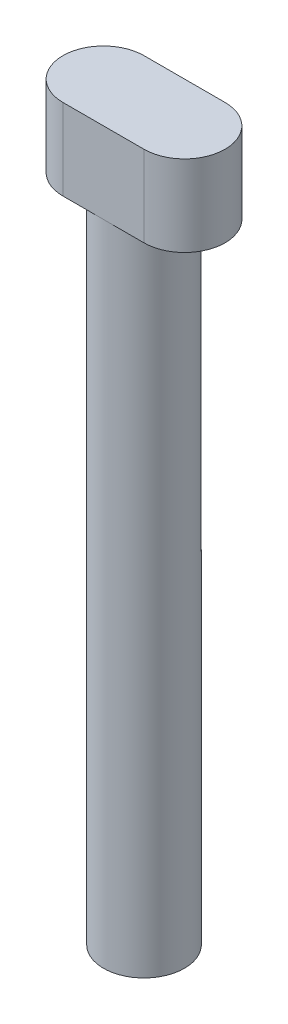
SolidWorks part; units mm, degrees
ref_plane "Front Plane" through (0, 0, 0) normal (0, 0, 1) x (1, 0, 0)
ref_plane "Top Plane" through (0, 0, 0) normal (0, 1, 0) x (1, 0, 0)
ref_plane "Right Plane" through (0, 0, 0) normal (1, 0, 0) x (0, 0, -1)
sketch "Sketch1" plane through (0, 0, 0) normal (0, 1, 0) x (1, 0, 0)
  line L1 (-7.2007, -3.175) -> (-5.4993, -3.175)
  line L2 (-7.2007, -3.175) -> (-7.2007, 3.175)
  line L3 (-7.2007, 3.175) -> (-5.4993, 3.175)
  line L4 (-5.4993, -3.175) -> (-5.4993, 3.175)
  line L5 (-7.2007, -3.175) -> (-5.4993, 3.175) construction
  line L6 (-7.2007, 3.175) -> (-5.4993, -3.175) construction
  circle A0 centre (0, 0) radius 6.35
  point P3 (-6.35, 0)
  dimension "D1" = 12.7
  dimension "D2" = 6.35
extrude "Boss-Extrude1" add sketch "Sketch1" against normal blind 101.6 contours L4 A0
sketch "Sketch4" plane through (0, 0, 0) normal (0, 1, 0) x (1, 0, 0)
  line L0 (-6.35, 0) -> (6.35, 0) construction
  line L1 (-6.35, 6.35) -> (6.35, 6.35)
  line L2 (-6.35, -6.35) -> (6.35, -6.35)
  arc A0 (-5.4993, -3.175) -> (-5.4993, 3.175) centre (0, 0) ccw construction
  arc A1 (-6.35, 6.35) -> (-6.35, -6.35) centre (-6.35, 0) ccw
  arc A2 (6.35, -6.35) -> (6.35, 6.35) centre (6.35, 0) ccw
  point P6 (0, 0)
  point P11 (0, 0)
  point P12 (6.35, 6.35)
extrude "Boss-Extrude3" add sketch "Sketch4" along normal blind 12.7
